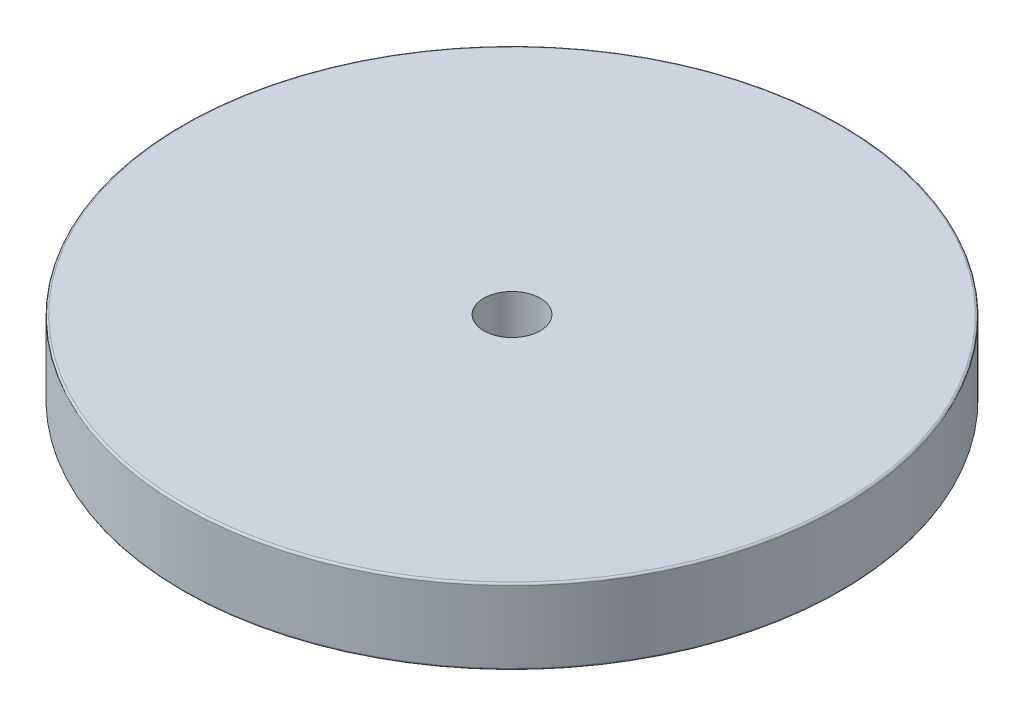
SolidWorks part; units mm, degrees
ref_plane "Front Plane" through (0, 0, 0) normal (0, 0, 1) x (1, 0, 0)
ref_plane "Top Plane" through (0, 0, 0) normal (0, 1, 0) x (1, 0, 0)
ref_plane "Right Plane" through (0, 0, 0) normal (1, 0, 0) x (0, 0, -1)
sketch "Sketch1" plane through (0, 0, 0) normal (0, 1, 0) x (1, 0, 0)
  circle A0 centre (0, 0) radius 175
  dimension "D1" = 350
extrude "Boss-Extrude1" add sketch "Sketch1" along normal blind 40
sketch "Sketch2" plane through (0, 40, 0) normal (0, 1, 0) x (1, 0, 0)
  circle A0 centre (0, 0) radius 15
  dimension "D1" = 30
extrude "Cut-Extrude1" cut sketch "Sketch2" against normal through all
fillet "Fillet1" radius 1 2 edges at (0, 0, 175) (0, 40, 175)
